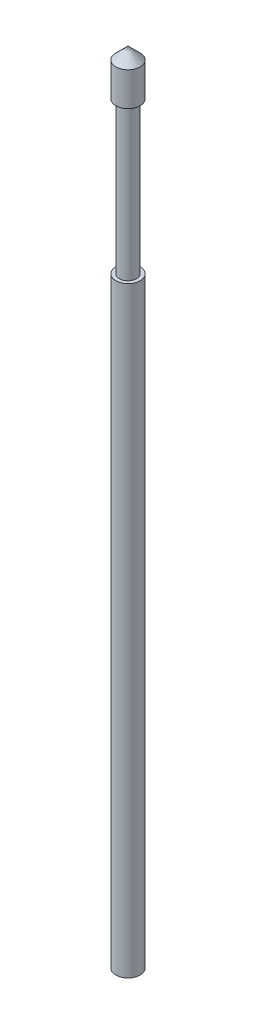
SolidWorks part; units mm, degrees
ref_plane "Front Plane" through (0, 0, 0) normal (0, 0, 1) x (1, 0, 0)
ref_plane "Top Plane" through (0, 0, 0) normal (0, 1, 0) x (1, 0, 0)
ref_plane "Right Plane" through (0, 0, 0) normal (1, 0, 0) x (0, 0, -1)
sketch "Sketch1" plane through (0, 0, 0) normal (0, 1, 0) x (1, 0, 0)
  circle A0 centre (0, 0) radius 0.505
  dimension "D1" = 1.01
extrude "Boss-Extrude1" add sketch "Sketch1" along normal blind 25
sketch "Sketch2" plane through (0, 25, 0) normal (0, 1, 0) x (1, 0, 0)
  circle A0 centre (0, 0) radius 0.36
  dimension "D1" = 0.72
extrude "Boss-Extrude2" add sketch "Sketch2" along normal blind 6.3
sketch "Sketch3" plane through (0, 31.3, 0) normal (0, 1, 0) x (1, 0, 0)
  circle A0 centre (0, 0) radius 0.505
  dimension "D1" = 1.01
extrude "Boss-Extrude3" add sketch "Sketch3" along normal blind 1.4
sketch "Sketch4" plane through (0, 0, 0) normal (0, 0, 1) x (1, 0, 0)
  line L0 (0, 32.7) -> (0, 33.2)
  line L1 (0, 33.2) -> (0.505, 32.7)
  line L2 (0.505, 32.7) -> (0, 32.7)
  line L3 (0.505, 32.7) -> (-0.505, 32.7) construction
  dimension "D1" = 0.5
  dimension "D2" = 0.505
revolve "Revolve1" add sketch "Sketch4" angle 360 about L0
equation "\"D1@Sketch4\"=33.3-25-6.4-1.4"
equation "\"D2@Sketch4\"=1.01mm/2"
